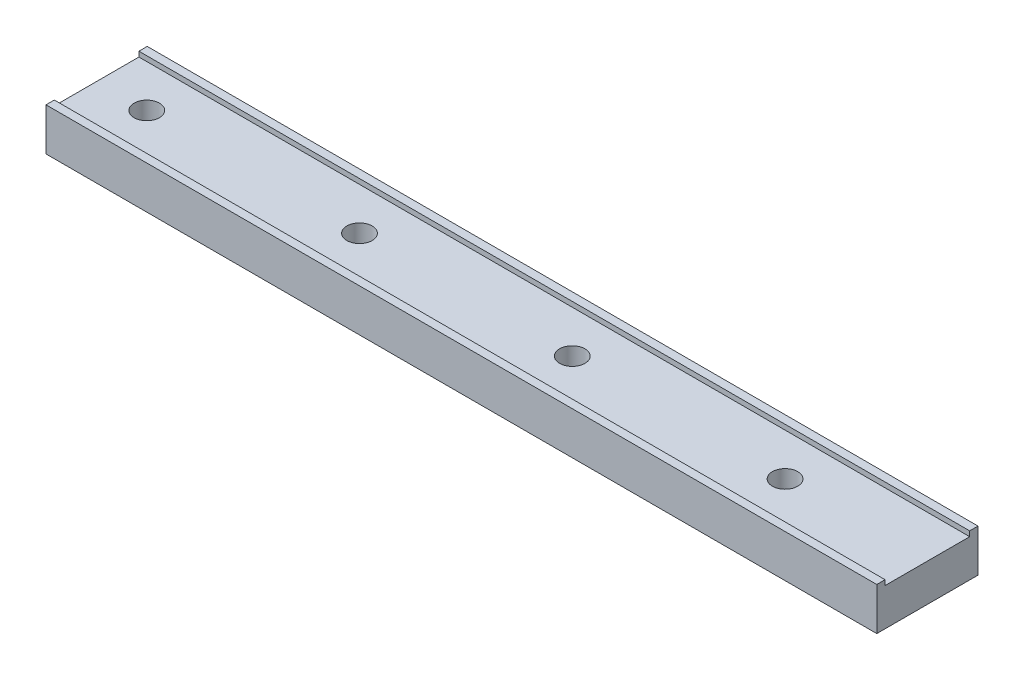
SolidWorks part; units mm, degrees
ref_plane "Front Plane" through (0, 0, 0) normal (0, 0, 1) x (1, 0, 0)
ref_plane "Top Plane" through (0, 0, 0) normal (0, 1, 0) x (1, 0, 0)
ref_plane "Right Plane" through (0, 0, 0) normal (1, 0, 0) x (0, 0, -1)
sketch "Sketch1" plane through (0, 0, 0) normal (0, 1, 0) x (1, 0, 0)
  line L1 (-104.14, -12.6873) -> (104.14, -12.6873)
  line L2 (-104.14, -12.6873) -> (-104.14, 12.6873)
  line L3 (-104.14, 12.6873) -> (104.14, 12.6873)
  line L4 (104.14, -12.6873) -> (104.14, 12.6873)
  line L5 (-104.14, -12.6873) -> (104.14, 12.6873) construction
  line L6 (-104.14, 12.6873) -> (104.14, -12.6873) construction
  circle A0 centre (-91.567, 0) radius 3.175
  circle A1 centre (-38.227, 0) radius 3.175
  circle A2 centre (15.113, 0) radius 3.175
  circle A3 centre (68.453, 0) radius 3.175
  point P0 (0, 0)
  dimension "D4" = 6.35
  dimension "D1" = 25.3746
  dimension "D2" = 208.28
  dimension "D3" = 12.573
  dimension "D5" = 4
extrude "Boss-Extrude1" add sketch "Sketch1" along normal blind 9.398
sketch "Sketch2" plane through (0, 9.398, 0) normal (0, 1, 0) x (1, 0, 0)
  line L0 (104.14, -12.6873) -> (104.14, 12.6873) construction
  line L1 (-104.14, 12.6873) -> (104.14, 12.6873)
  line L2 (-104.14, 12.6873) -> (-104.14, 10.6045)
  line L3 (-104.14, 10.6045) -> (104.14, 10.6045)
  line L4 (104.14, 12.6873) -> (104.14, 10.6045)
  line L6 (-104.14, -12.6873) -> (104.14, -12.6873)
  line L7 (-104.14, -12.6873) -> (-104.14, -10.6045)
  line L8 (-104.14, -10.6045) -> (104.14, -10.6045)
  line L9 (104.14, -12.6873) -> (104.14, -10.6045)
  dimension "D1" = 21.209
extrude "Boss-Extrude2" add sketch "Sketch2" along normal blind 1.27
equation "\"Width\"=0.999"
equation "\"D1@Sketch1\"=\"Width\""
equation "\"Length\"=8.2"
equation "\"D2@Sketch1\"=\"Length\""
equation "\"HoleDistance\"= 0.37 + \"HoleDiameter\" / 2"
equation "\"D3@Sketch1\"=\"HoleDistance\""
equation "\"HoleDiameter\"=0.25"
equation "\"D4@Sketch1\"=\"HoleDiameter\""
equation "\"SpacedHeight\"=0.37"
equation "\"D1@Boss-Extrude1\"=\"SpacedHeight\""
equation "\"DistBetweenLips\"=0.835"
equation "\"D1@Sketch2\"=\"DistBetweenLips\""
